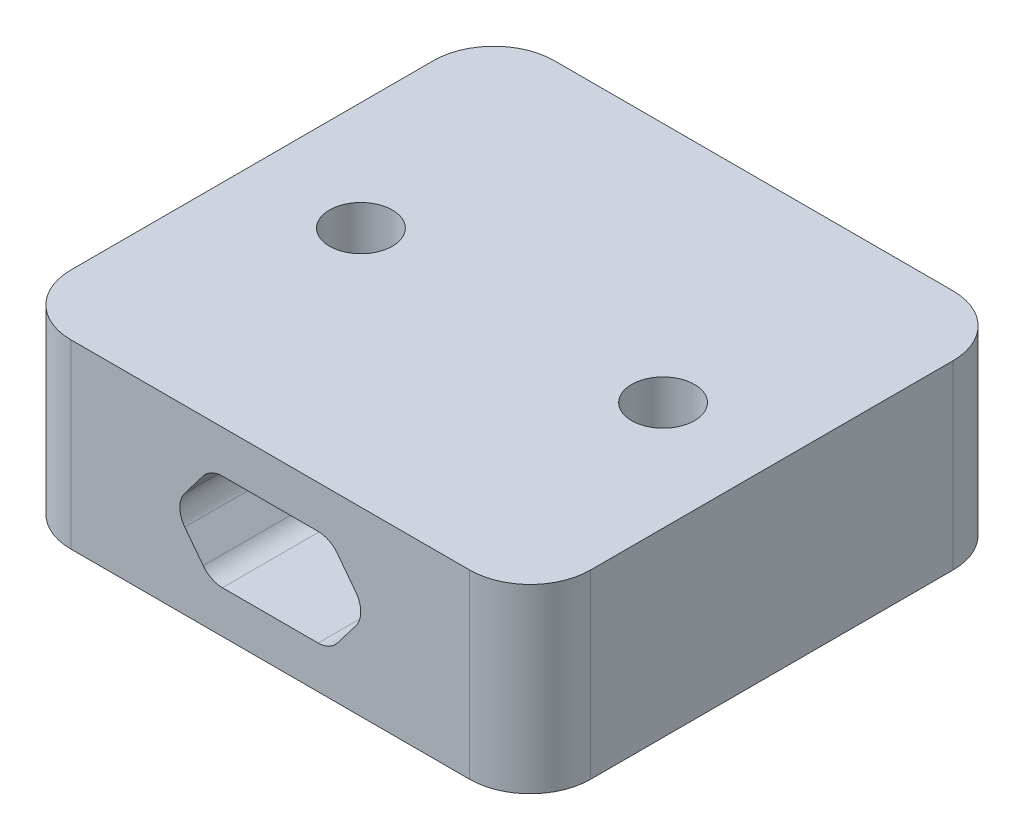
SolidWorks part; units mm, degrees
ref_plane "Front Plane" through (0, 0, 0) normal (0, 0, 1) x (1, 0, 0)
ref_plane "Top Plane" through (0, 0, 0) normal (0, 1, 0) x (1, 0, 0)
ref_plane "Right Plane" through (0, 0, 0) normal (1, 0, 0) x (0, 0, -1)
sketch "Sketch1" plane through (0, 0, 0) normal (0, 1, 0) x (1, 0, 0)
  line L1 (0, 0) -> (43, 0)
  line L2 (0, 0) -> (0, 40)
  line L3 (0, 40) -> (43, 40)
  line L4 (43, 0) -> (43, 40)
  dimension "D1" = 43
  dimension "D2" = 40
extrude "Boss-Extrude1" add sketch "Sketch1" along normal blind 15
sketch "Sketch2" plane through (0, 0, 0) normal (0, 0, 1) x (1, 0, 0)
  line L0 (0, 7.5) -> (43, 7.5) construction
  line L1 (0, 15) -> (0, 0) construction
  line L2 (43, 15) -> (43, 0) construction
  line L3 (21.5, 7.5) -> (21.5, 11.5) construction
  line L4 (13.5, 7.5) -> (16.55, 11.5)
  line L5 (16.55, 11.5) -> (26.45, 11.5)
  line L6 (29.5, 7.5) -> (26.45, 11.5)
  line L7 (29.5, 7.5) -> (26.45, 3.5)
  line L8 (16.55, 3.5) -> (26.45, 3.5)
  line L9 (13.5, 7.5) -> (16.55, 3.5)
  dimension "D1" = 16
  dimension "D2" = 9.9
  dimension "D3" = 4
extrude "Cut-Extrude1" cut sketch "Sketch2" against normal blind 25
sketch "Sketch3" plane through (0, 0, 0) normal (0, 0, 1) x (1, 0, 0)
  line L0 (13.5, 7.5) -> (29.5, 7.5) construction
  circle A0 centre (21.5, 7.5) radius 3
  dimension "D1" = 6
extrude "Cut-Extrude2" cut sketch "Sketch3" against normal through all
sketch "Sketch4" plane through (0, 0, 0) normal (0, 1, 0) x (1, 0, 0)
  line L0 (9, 20) -> (34, 20) construction
  line L2 (21.5, 40) -> (21.5, 0) construction
  line L3 (43, 40) -> (0, 40) construction
  line L4 (0, 0) -> (43, 0) construction
  circle A0 centre (9, 20) radius 2.6
  circle A1 centre (34, 20) radius 2.6
  point P11 (21.5, 20)
  dimension "D4" = 5.2
  dimension "D5" = 5.2
  dimension "D1" = 20
  dimension "D2" = 25
extrude "Cut-Extrude3" cut sketch "Sketch4" along normal through all
fillet "Fillet1" radius 2 6 edges at (16.55, 3.5, -12.5) (26.45, 3.5, -12.5) (29.5, 7.5, -12.5) (26.45, 11.5, -12.5) (16.55, 11.5, -12.5) (13.5, 7.5, -12.5)
fillet "Fillet3" radius 5 4 edges at (43, 7.5, -40) (43, 7.5, 0) (0, 7.5, -40) (0, 7.5, 0)
sketch "Sketch6" plane through (0, 0, -40) normal (0, 0, 1) x (1, 0, 0)
  line L0 (26.9, 10.6177) -> (26.9, 15)
  line L1 (16.1, 10.6177) -> (16.1, 4.3823)
  line L2 (16.1, 4.3823) -> (21.5, 1.2646)
  line L3 (21.5, 1.2646) -> (26.9, 4.3823)
  line L4 (26.9, 4.3823) -> (26.9, 10.6177)
  line L5 (26.9, 10.6177) -> (21.5, 13.7354) construction
  line L6 (21.5, 13.7354) -> (16.1, 10.6177) construction
  line L7 (38, 15) -> (5, 15) construction
  line L8 (26.9, 15) -> (16.1, 15)
  line L9 (16.1, 10.6177) -> (16.1, 15)
  circle A0 centre (21.5, 7.5) radius 5.4 construction
  dimension "D1" = 10.8
